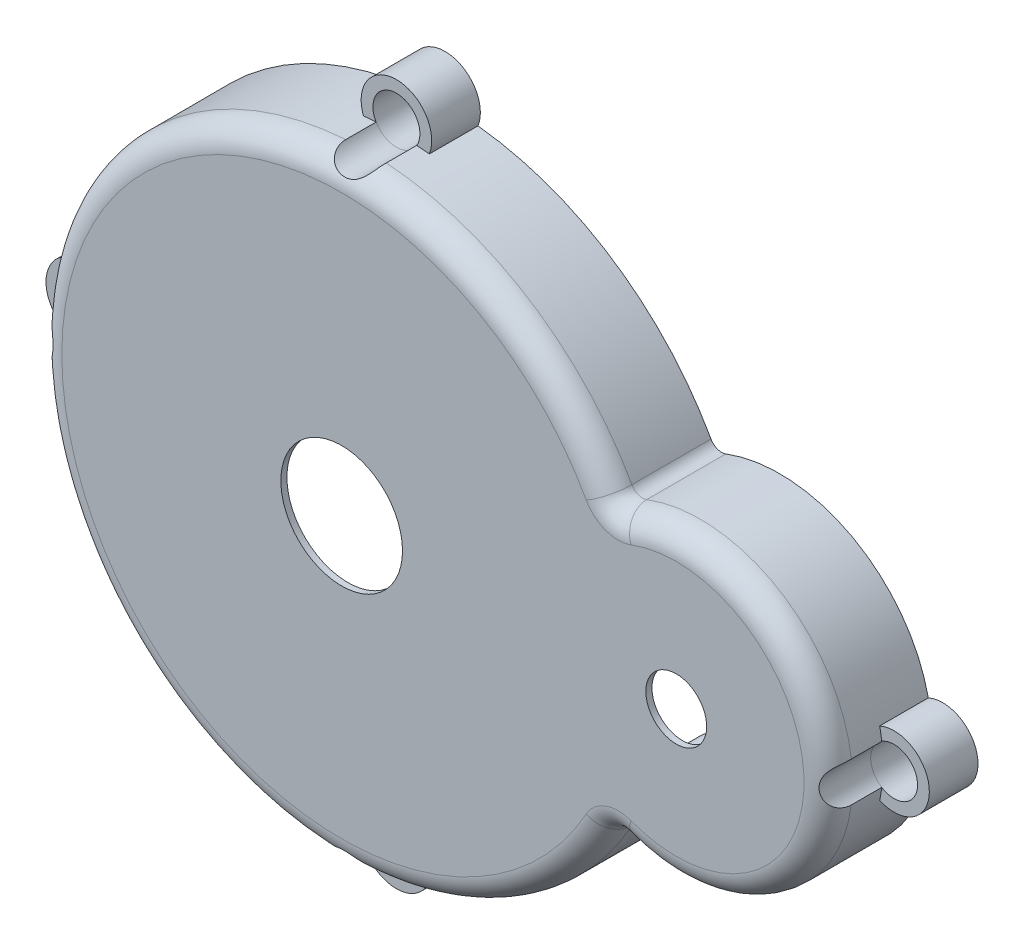
SolidWorks part; units mm, degrees
ref_plane "Front Plane" through (0, 0, 0) normal (0, 0, 1) x (1, 0, 0)
ref_plane "Top Plane" through (0, 0, 0) normal (0, 1, 0) x (1, 0, 0)
ref_plane "Right Plane" through (0, 0, 0) normal (1, 0, 0) x (0, 0, -1)
sketch "Sketch1" plane through (0, 0, 0) normal (0, 0, 1) x (1, 0, 0)
  line L0 (-4.7625, 0) -> (-30.1625, 0)
  circle A0 centre (0, 0) radius 4.7625
  circle A1 centre (-17.4625, 0) radius 12.7
  circle A2 centre (0, 0) radius 6.6675
  circle A3 centre (-17.4625, 0) radius 14.605
  circle A4 centre (-17.4625, 0) radius 15.875
  circle A5 centre (0, 0) radius 7.9375
  dimension "D1" = 9.525
  dimension "D2" = 25.4
  dimension "D3" = 1.905
  dimension "D4" = 1.27
extrude "Boss-Extrude1" add sketch "Sketch1" along normal blind 2.54 contours A5 A4 A3 | A4 A5 A2 | A4 A5 A3 A2 | A3 A5 A4 A2 | A0
fillet "Fillet1" radius 0.635 4 edges at (-3.3193, 7.2101, 1.27) (-3.3193, -7.2101, 1.27) (-3.8966, 5.4104, 1.27) (-3.8966, -5.4104, 1.27)
sketch "Sketch5" plane through (0, 0, 2.54) normal (0, 0, 1) x (1, 0, 0)
  circle A0 centre (0, 0) radius 1.5875
  circle A1 centre (-17.4625, 0) radius 3.175
  arc M1 (-3.5858, 7.7105) -> (-3.5858, -7.7105) centre (-17.4625, 0) ccw
  arc M2 (-3.5858, -7.7105) -> (-2.8062, -7.4249) centre (-3.0307, -8.0189) cw
  arc M3 (-2.8062, -7.4249) -> (-2.8062, 7.4249) centre (0, 0) ccw
  arc M4 (-2.8062, 7.4249) -> (-3.5858, 7.7105) centre (-3.0307, 8.0189) cw
  arc M5 (-3.2942, 5.7969) -> (-3.2942, -5.7969) centre (0, 0) cw
  arc M6 (-3.2942, -5.7969) -> (-4.1852, -6.0844) centre (-3.608, -6.349) ccw
  arc M7 (-4.1852, -6.0844) -> (-4.1852, 6.0844) centre (-17.4625, 0) cw
  arc M8 (-4.1852, 6.0844) -> (-3.2942, 5.7969) centre (-3.608, 6.349) ccw
  dimension "D1" = 3.175
  dimension "D2" = 6.35
extrude "Boss-Extrude2" add sketch "Sketch5" along normal blind 0.3175 contours M4 M1 M2 M3 M8 M5 M6 M7 | A0 M5 M8 M7 M6
fillet "Fillet2" radius 1.27 4 edges at (-3.2491, -7.4226, 2.8575) (-3.2491, 7.4226, 2.8575) (-33.3375, 0, 2.8575) (7.9375, 0, 2.8575)
sketch "Sketch7" plane through (0, 0, 0) normal (0, 0, -1) x (-1, 0, 0)
  line L0 (-6.6675, 0) -> (-8.509, 0)
  line L1 (17.4625, 14.605) -> (17.4625, 16.4465)
  line L2 (32.0675, 0) -> (33.909, 0)
  line L3 (17.4625, -14.605) -> (17.4625, -16.4465)
  arc A1 (3.2942, 5.7969) -> (3.2942, -5.7969) centre (0, 0) ccw construction
  circle A3 centre (-8.509, 0) radius 1.8415
  arc A4 (4.1852, -6.0844) -> (4.1852, 6.0844) centre (17.4625, 0) ccw construction
  arc A5 (4.1852, -6.0844) -> (4.1852, 6.0844) centre (17.4625, 0) ccw construction
  circle A7 centre (17.4625, 16.4465) radius 1.8415
  circle A8 centre (33.909, 0) radius 1.8415
  circle A9 centre (17.4625, -16.4465) radius 1.8415
  circle A10 centre (17.4625, 16.4465) radius 1.2255
  circle A11 centre (-8.509, 0) radius 1.2255
  circle A12 centre (17.4625, -16.4465) radius 1.2255
  circle A13 centre (33.909, 0) radius 1.2255
  arc M4 (2.8062, 7.4249) -> (2.8062, -7.4249) centre (0, 0) ccw
  arc M5 (2.8062, -7.4249) -> (3.5858, -7.7105) centre (3.0307, -8.0189) cw
  arc M6 (3.5858, -7.7105) -> (3.5858, 7.7105) centre (17.4625, 0) ccw
  arc M7 (3.5858, 7.7105) -> (2.8062, 7.4249) centre (3.0307, 8.0189) cw
  arc M8 (4.1852, 6.0844) -> (4.1852, -6.0844) centre (17.4625, 0) cw
  arc M9 (4.1852, -6.0844) -> (3.2942, -5.7969) centre (3.608, -6.349) ccw
  arc M10 (3.2942, -5.7969) -> (3.2942, 5.7969) centre (0, 0) cw
  arc M11 (3.2942, 5.7969) -> (4.1852, 6.0844) centre (3.608, 6.349) ccw
  dimension "D1" = 1.8415
  dimension "D5" = 2.4511
  dimension "D6" = 2.4511
  dimension "D7" = 2.4511
  dimension "D8" = 2.4511
  dimension "D2" = 1.8415
  dimension "D3" = 1.8415
  dimension "D4" = 1.8415
extrude "Boss-Extrude3" add sketch "Sketch7" along normal blind 2.54 contours A7 A3 M6 M7 M4 M10 M11 M8 | A9 A3 M8 M9 M10 M4 M5 M6 | A11 A3 M4 | A11 A3 L0 M4 | A11 L0 A3 M4 | A9 A8 M6 M8 | A12 L3 A9 M6 | A12 A9 L3 M6 | A12 A9 M6 | A8 A7 M6 M8 | A10 A7 M6 | A10 L1 A7 M6 | A10 A7 L1 M6 | A13 A8 M6 | A13 A8 L2 M6 | A13 L2 A8 M6
sketch "Sketch13" plane through (0, 0, 0) normal (0, 0, -1) x (-1, 0, 0)
  circle A0 centre (-8.509, 0) radius 1.2192
  circle A1 centre (17.4625, 16.4465) radius 1.2192
  circle A2 centre (33.909, 0) radius 1.2192
  circle A3 centre (17.4625, -16.4465) radius 1.2192
extrude "Cut-Extrude7" cut sketch "Sketch13" against normal through all
equation "\"Do\" = 0.25in"
equation "\"Di\"=0.125"
equation "\"L1\"= 1"
equation "\"t\"= 0.9375 / ( 2 * \"Do\" * 1000 )"
equation "\"ODo\"= ( 2 * \"t\" ) + \"Do\""
equation "\"ODi\"= ( 2 * \"t\" ) + \"Di\""
equation "\"D1@Boss-Extrude1\"=0.1"
equation "\"D1@Sketch5\"=\"Di\""
equation "\"D2@Sketch5\"= \"Do\""
